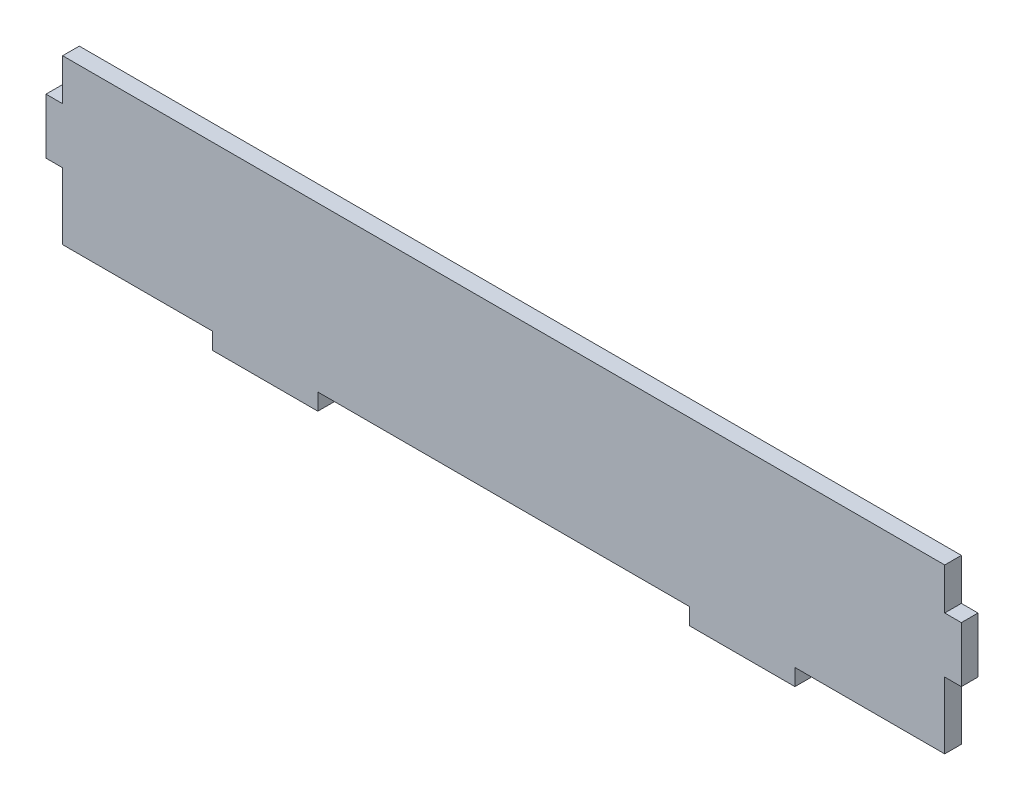
SolidWorks part; units mm, degrees
ref_plane "Plan de face" through (0, 0, 0) normal (0, 0, 1) x (1, 0, 0)
ref_plane "Plan de dessus" through (0, 0, 0) normal (0, 1, 0) x (1, 0, 0)
ref_plane "Plan de droite" through (0, 0, 0) normal (1, 0, 0) x (0, 0, -1)
sketch "Esquisse1" plane through (0, 0, 0) normal (0, 0, 1) x (1, 0, 0)
  line L1 (0, 0) -> (-330, 0)
  line L2 (0, 0) -> (0, 65)
  line L3 (0, 65) -> (-330, 65)
  line L4 (-330, 0) -> (-330, 65)
  dimension "D1" = 330
  dimension "D2" = 65
extrude "Boss.-Extru.1" add sketch "Esquisse1" along normal blind 6
sketch "Esquisse2" plane through (0, 0, 6) normal (0, 0, 1) x (1, 0, 0)
  line L0 (-330, 0) -> (0, 0) construction
  line L1 (-330, 0) -> (-270, 0)
  line L2 (-330, 30) -> (-330, 0)
  line L3 (-324, 6) -> (-270, 6)
  line L4 (-270, 0) -> (-270, 6)
  line L5 (0, 0) -> (-60, 0)
  line L6 (0, 30) -> (0, 0)
  line L7 (-6, 6) -> (-60, 6)
  line L8 (-60, 0) -> (-60, 6)
  line L9 (-232, 0) -> (-98, 0)
  line L10 (-232, 0) -> (-232, 6)
  line L11 (-232, 6) -> (-98, 6)
  line L12 (-98, 0) -> (-98, 6)
  line L16 (-330, 30) -> (-324, 30)
  line L17 (-324, 6) -> (-324, 30)
  line L18 (-330, 65) -> (-324, 65)
  line L19 (-330, 65) -> (-330, 50)
  line L20 (-330, 50) -> (-324, 50)
  line L21 (-324, 65) -> (-324, 50)
  line L22 (0, 65) -> (-6, 65)
  line L23 (0, 65) -> (0, 50)
  line L24 (0, 50) -> (-6, 50)
  line L25 (-6, 65) -> (-6, 50)
  line L28 (0, 30) -> (-6, 30)
  line L29 (-6, 6) -> (-6, 30)
  dimension "D2" = 6
  dimension "D3" = 6
  dimension "D4" = 134
  dimension "D5" = 38
  dimension "D6" = 38
  dimension "D7" = 6
  dimension "D8" = 20
  dimension "D9" = 15
  dimension "D10" = 6
  dimension "D11" = 6
  dimension "D12" = 60
  dimension "D13" = 20
  dimension "D14" = 6
  dimension "D15" = 6
  dimension "D16" = 15
extrude "Enlèv. mat.-Extru.1" cut sketch "Esquisse2" against normal blind 6
